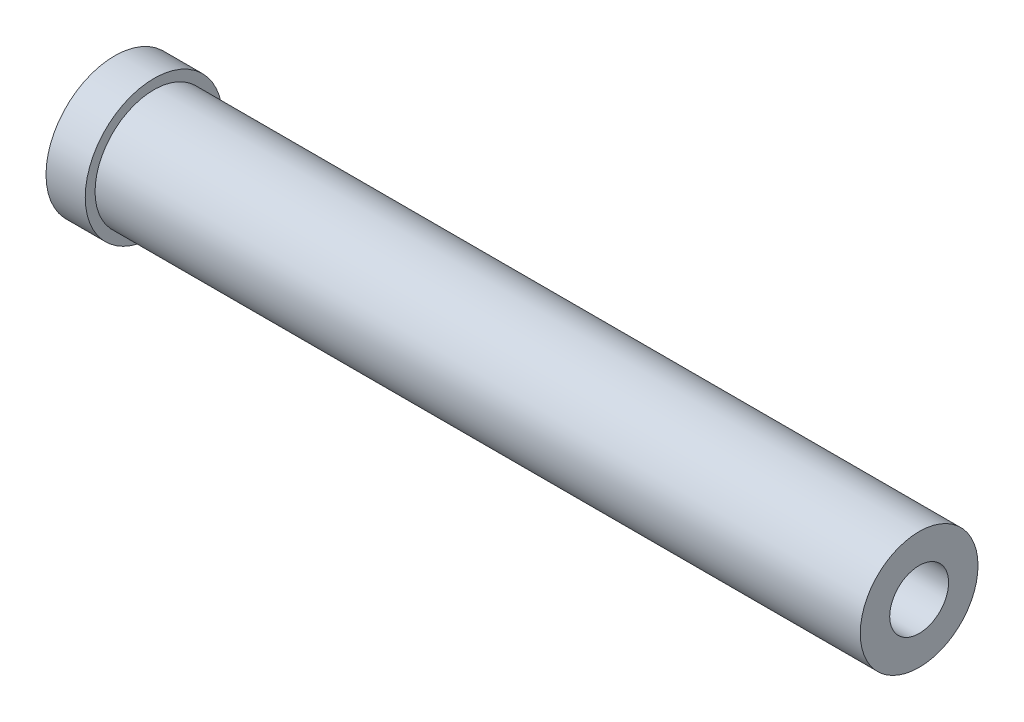
SolidWorks part; units mm, degrees
material "1060 Alloy"
ref_plane "Front Plane" through (0, 0, 0) normal (0, 0, 1) x (1, 0, 0)
ref_plane "Top Plane" through (0, 0, 0) normal (0, 1, 0) x (1, 0, 0)
ref_plane "Right Plane" through (0, 0, 0) normal (1, 0, 0) x (0, 0, -1)
sketch "Sketch1" plane through (0, 0, 0) normal (1, 0, 0) x (0, 0, -1)
  circle A0 centre (0, 0) radius 3.81
  circle A1 centre (0, 0) radius 1.905
  dimension "D1" = 7.62
  dimension "D2" = 3.81
extrude "Boss-Extrude1" add sketch "Sketch1" along normal mid plane 50.8
sketch "Sketch2" plane through (-25.4, 0, 0) normal (-1, 0, 0) x (0, 0, 1)
  circle A0 centre (0, 0) radius 4.445
  dimension "D1" = 8.89
extrude "Boss-Extrude2" add sketch "Sketch2" along normal mid plane 2.54
